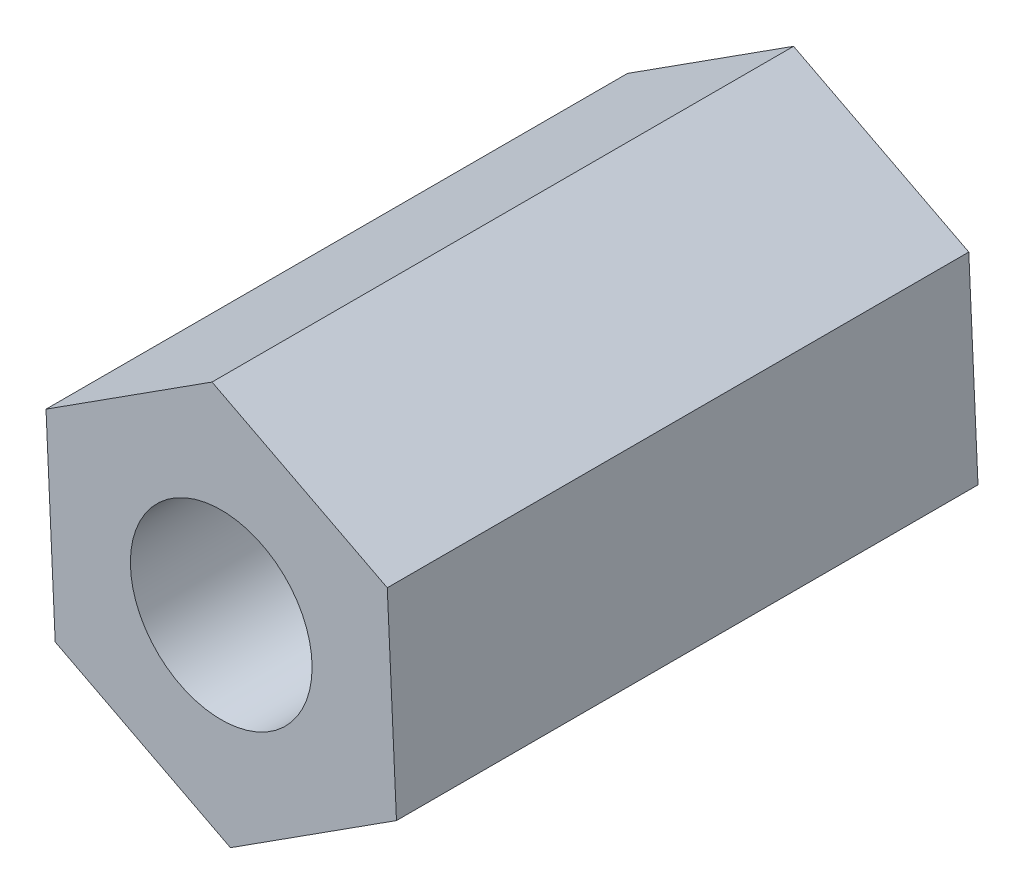
SolidWorks part; units mm, degrees
material "普通碳钢"
ref_plane "前视基准面" through (0, 0, 0) normal (0, 0, 1) x (1, 0, 0)
ref_plane "上视基准面" through (0, 0, 0) normal (0, 1, 0) x (1, 0, 0)
ref_plane "右视基准面" through (0, 0, 0) normal (1, 0, 0) x (0, 0, -1)
sketch "草图1" plane through (0, 0, 0) normal (0, 0, 1) x (1, 0, 0)
  line L1 (-0.1266, 2.7106) -> (-2.4107, 1.2457)
  line L2 (-2.4107, 1.2457) -> (-2.2841, -1.4649)
  line L3 (-2.2841, -1.4649) -> (0.1266, -2.7106)
  line L4 (0.1266, -2.7106) -> (2.4107, -1.2457)
  line L5 (2.4107, -1.2457) -> (2.2841, 1.4649)
  line L6 (2.2841, 1.4649) -> (-0.1266, 2.7106)
  circle A1 centre (0, 0) radius 2.35 construction
  dimension "D1" = 4.7
extrude "凸台-拉伸1" add sketch "草图1" along normal blind 8
hole_wizard "M3 螺纹孔1" positions "3D草图3" profile "草图5" tap size "M3" standard "GB" end condition through all
sketch3d "3D草图3"
  point P0 (0, 0, 0)
  point P5 (0, 0, 0)
  point P7 (0, 0, 0)
sketch "草图5" plane through (0, 0, 0) normal (1, 0, 0) x (0, 1, 0)
  line L0 (0, 0) -> (0, 8)
  line L1 (0, 8) -> (1.25, 8)
  line L2 (1.25, 8) -> (1.25, 0)
  line L5 (1.25, 0) -> (0, 0)
  line L11 (0, -6.35) -> (0, 107.95) construction
  dimension "通孔螺纹孔钻头直径" = 2.5
  dimension "通孔螺纹孔钻头深度" = 8
cosmetic thread "孔螺蚊线1"
cosmetic thread "孔螺蚊线2"
cosmetic thread "孔螺蚊线3"
